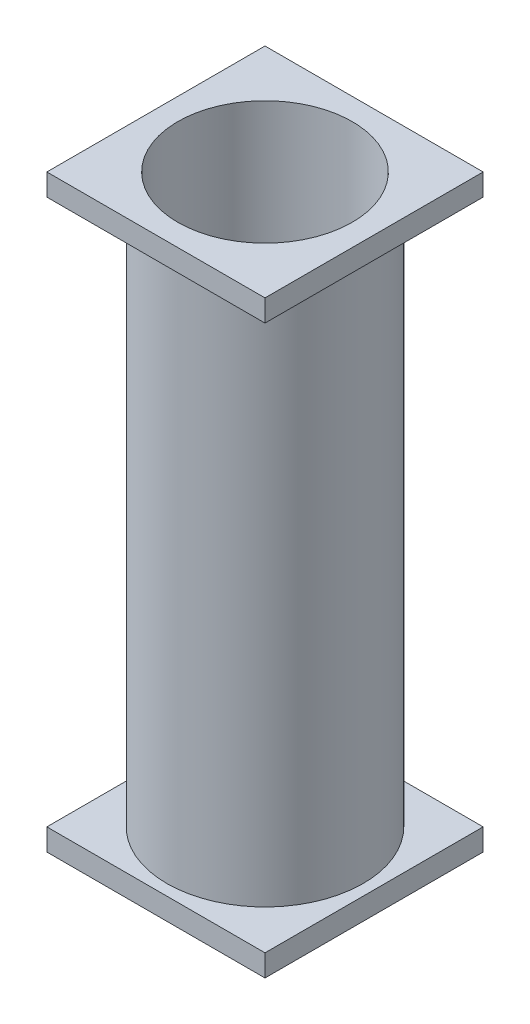
SolidWorks part; units mm, degrees
ref_plane "Front Plane" through (0, 0, 0) normal (0, 0, 1) x (1, 0, 0)
ref_plane "Top Plane" through (0, 0, 0) normal (0, 1, 0) x (1, 0, 0)
ref_plane "Right Plane" through (0, 0, 0) normal (1, 0, 0) x (0, 0, -1)
sketch "Sketch1" plane through (0, 0, 0) normal (0, 1, 0) x (1, 0, 0)
  line L1 (0, 0) -> (-20, 0)
  line L2 (0, 0) -> (0, 20)
  line L3 (0, 20) -> (-20, 20)
  line L4 (-20, 0) -> (-20, 20)
  circle A0 centre (-10, 10) radius 8
  dimension "D3" = 16
  dimension "D1" = 20
  dimension "D2" = 20
extrude "Boss-Extrude1" add sketch "Sketch1" along normal blind 2
sketch "Sketch2" plane through (0, 2, 0) normal (0, 1, 0) x (1, 0, 0)
  line L0 (-18, 10) -> (-2, 10)
  circle A0 centre (-10, 10) radius 8 construction
  circle A1 centre (-10, 10) radius 8
  circle A2 centre (-10, 10) radius 9
  dimension "D1" = 16
  dimension "D2" = 18
extrude "Boss-Extrude3" add sketch "Sketch2" along normal blind 50
sketch "Sketch3" plane through (0, 52, 0) normal (0, 1, 0) x (1, 0, 0)
  line L1 (0, 20) -> (-20, 20)
  line L2 (0, 20) -> (0, 0)
  line L3 (0, 0) -> (-20, 0)
  line L4 (-20, 20) -> (-20, 0)
  circle A0 centre (-10, 10) radius 8
  dimension "D1" = 16
extrude "Boss-Extrude5" add sketch "Sketch3" along normal blind 2
